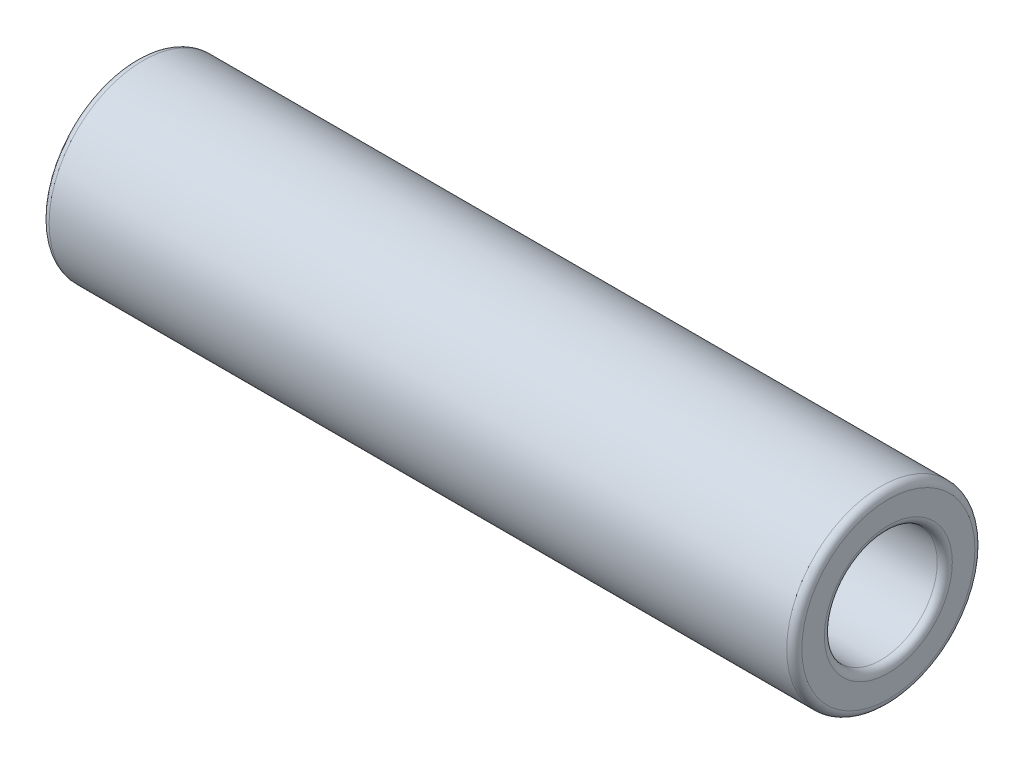
SolidWorks part; units mm, degrees
ref_plane "Front Plane" through (0, 0, 0) normal (0, 0, 1) x (1, 0, 0)
ref_plane "Top Plane" through (0, 0, 0) normal (0, 1, 0) x (1, 0, 0)
ref_plane "Right Plane" through (0, 0, 0) normal (1, 0, 0) x (0, 0, -1)
sketch "Sketch1" plane through (0, 0, 0) normal (1, 0, 0) x (0, 0, -1)
  circle A0 centre (0, 0) radius 3.75
  circle A1 centre (0, 0) radius 6.25
  dimension "D1" = 12.5
  dimension "D2" = 7.5
extrude "Boss-Extrude1" add sketch "Sketch1" along normal blind 50
fillet "Fillet1" radius 0.5 4 edges at (50, 0, -3.75) (50, 0, -6.25) (0, 0, -3.75) (0, 0, -6.25)
